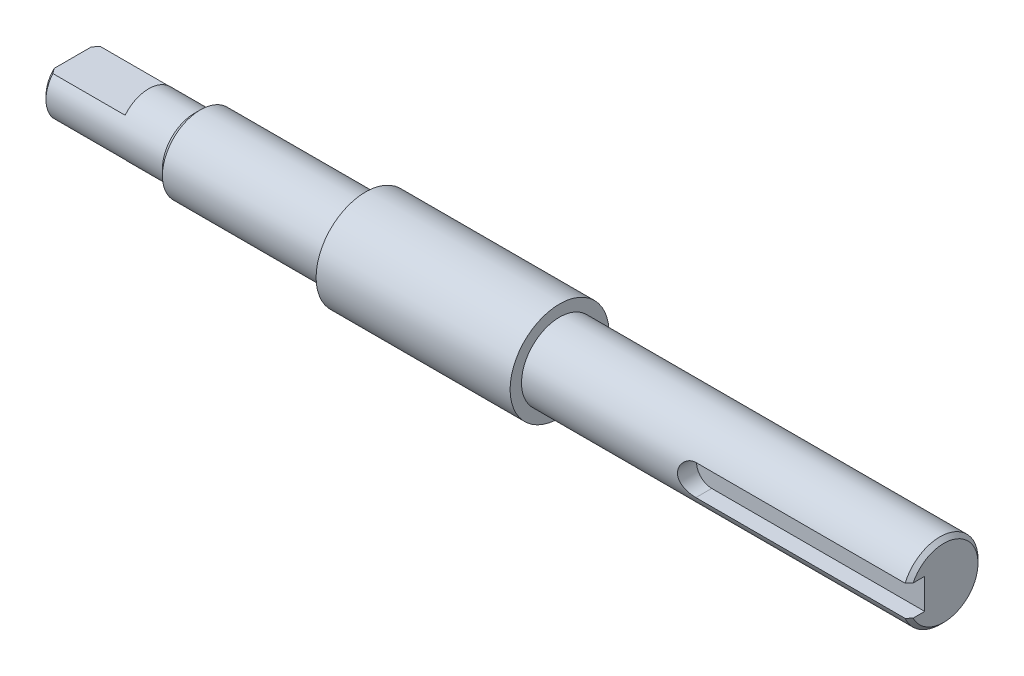
SolidWorks part; units mm, degrees
ref_plane "Front" through (0, 0, 0) normal (0, 0, 1) x (1, 0, 0)
ref_plane "Top" through (0, 0, 0) normal (0, 1, 0) x (1, 0, 0)
ref_plane "Right" through (0, 0, 0) normal (1, 0, 0) x (0, 0, -1)
sketch "Sketch1" plane through (0, 0, 0) normal (0, 0, 1) x (1, 0, 0)
  line L0 (-44.1945, 0) -> (87.487, 0) construction
  line L1 (-38.5, 0) -> (-38.5, 4)
  line L2 (-38.5, 4) -> (-22.5, 4)
  line L3 (-22.5, 4) -> (-22.5, 5)
  line L4 (-22.5, 5) -> (0, 5)
  line L5 (0, 6.5) -> (25.5, 6.5)
  line L6 (25.5, 6.5) -> (25.5, 5)
  line L7 (25.5, 5) -> (76, 5)
  line L8 (76, 5) -> (76, 0)
  line L9 (76, 0) -> (-38.5, 0)
  line L10 (0, 6.5) -> (0, 5)
  dimension "D1" = 8
  dimension "D2" = 10
  dimension "D3" = 13
  dimension "D4" = 38.5
  dimension "D5" = 22.5
  dimension "D6" = 25.5
  dimension "D7" = 76
revolve "Revolve1" add sketch "Sketch1" angle 360 about L0
cosmetic thread "Cosmetic Thread1" parameters "D1"=20, "D2"=8.5
sketch "Sketch2" plane through (-38.5, 0, 0) normal (-1, 0, 0) x (0, 0, 1)
  line L0 (-3.1, -2.5278) -> (3.1, -2.5278)
  line L1 (-3.1, 2.5278) -> (3.1, 2.5278)
  line L2 (-6.9478, 0) -> (7.195, 0) construction
  circle A0 centre (0, 0) radius 4 construction
  arc A1 (-3.1, -2.5278) -> (3.1, -2.5278) centre (0, 0) ccw
  arc A2 (3.1, 2.5278) -> (-3.1, 2.5278) centre (0, 0) ccw
  dimension "D1" = 5.0557
extrude "Cut-Extrude1" cut sketch "Sketch2" against normal blind 10
ref_plane "Plane1" through (0, 0, 5) normal (0, 0, 1) x (1, 0, 0)
sketch "Sketch3" plane through (0, 0, 5) normal (0, 0, 1) x (1, 0, 0)
  line L0 (-24.6884, 0) -> (105.4631, 0) construction
  line L2 (76, 0) -> (48, 0) construction
  line L3 (76, -2) -> (48, -2)
  line L4 (76, 2) -> (48, 2)
  line L6 (0, 6.5) -> (0, -6.5) construction
  line L7 (76, -5) -> (76, 5) construction
  arc A0 (76, -2) -> (76, 2) centre (76, 0) ccw
  arc A1 (48, 2) -> (48, -2) centre (48, 0) ccw
  point P5 (62, 0)
  dimension "D1" = 30
  dimension "D2" = 4
  dimension "D3" = 46
extrude "Cut-Extrude2" cut sketch "Sketch3" against normal blind 2.5
chamfer "Chamfer1" distance 0.8 angle 45 1 edges at (-22.5, 0, 5)
chamfer "Chamfer2" distance 0.5 angle 45 3 edges at (-38.5, 0, 4) (-38.5, 0, -4) (76, 0, -5)
